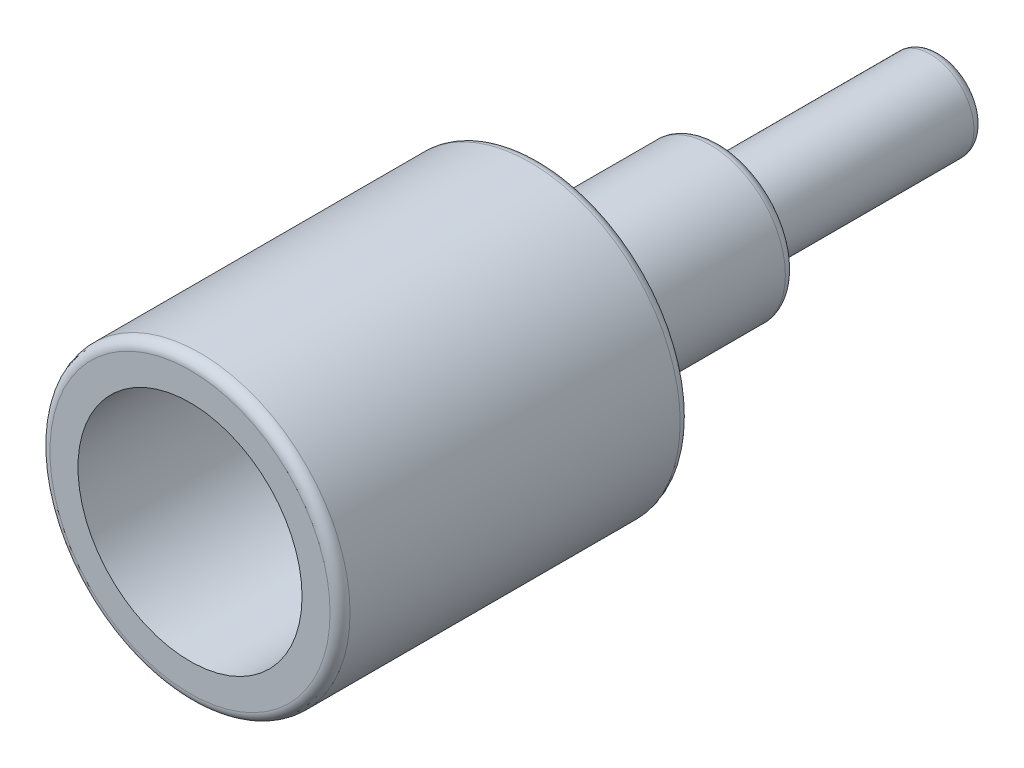
SolidWorks part; units mm, degrees
ref_plane "Front Plane" through (0, 0, 0) normal (0, 0, 1) x (1, 0, 0)
ref_plane "Top Plane" through (0, 0, 0) normal (0, 1, 0) x (1, 0, 0)
ref_plane "Right Plane" through (0, 0, 0) normal (1, 0, 0) x (0, 0, -1)
sketch "Sketch1" plane through (0, 0, 0) normal (0, 0, 1) x (1, 0, 0)
  circle A0 centre (0, 0) radius 1.5
  dimension "D1" = 3
extrude "Boss-Extrude1" add sketch "Sketch1" along normal blind 3.5
sketch "Sketch2" plane through (0, 0, 3.5) normal (0, 0, 1) x (1, 0, 0)
  circle A0 centre (0, 0) radius 1.12
  dimension "D1" = 2.24
extrude "Cut-Extrude1" cut sketch "Sketch2" against normal blind 3
sketch "Sketch3" plane through (0, 0, 0) normal (0, 0, -1) x (-1, 0, 0)
  circle A0 centre (0, 0) radius 0.7515
  dimension "D1" = 1.503
extrude "Boss-Extrude2" add sketch "Sketch3" along normal blind 1.8
sketch "Sketch4" plane through (0, 0, -1.8) normal (0, 0, -1) x (-1, 0, 0)
  circle A0 centre (0, 0) radius 0.4365
  dimension "D1" = 0.873
extrude "Boss-Extrude3" add sketch "Sketch4" along normal blind 2.2
fillet "Fillet1" radius 0.1 6 edges at (-0.7515, 0, 0) (-0.4365, 0, -4) (-0.7515, 0, -1.8) (1.5, 0, 0) (-0.4365, 0, -1.8) (1.5, 0, 3.5)
equation "\"D1@Boss-Extrude1\"=2mm"
equation "\"D1@Cut-Extrude1\"=3mm"
equation "\"D1@Sketch3\"=1.63-0.127"
equation "\"D1@Sketch4\"=1-0.127mm"
equation "\"D1@Sketch2\"=2.30-0.06mm"
